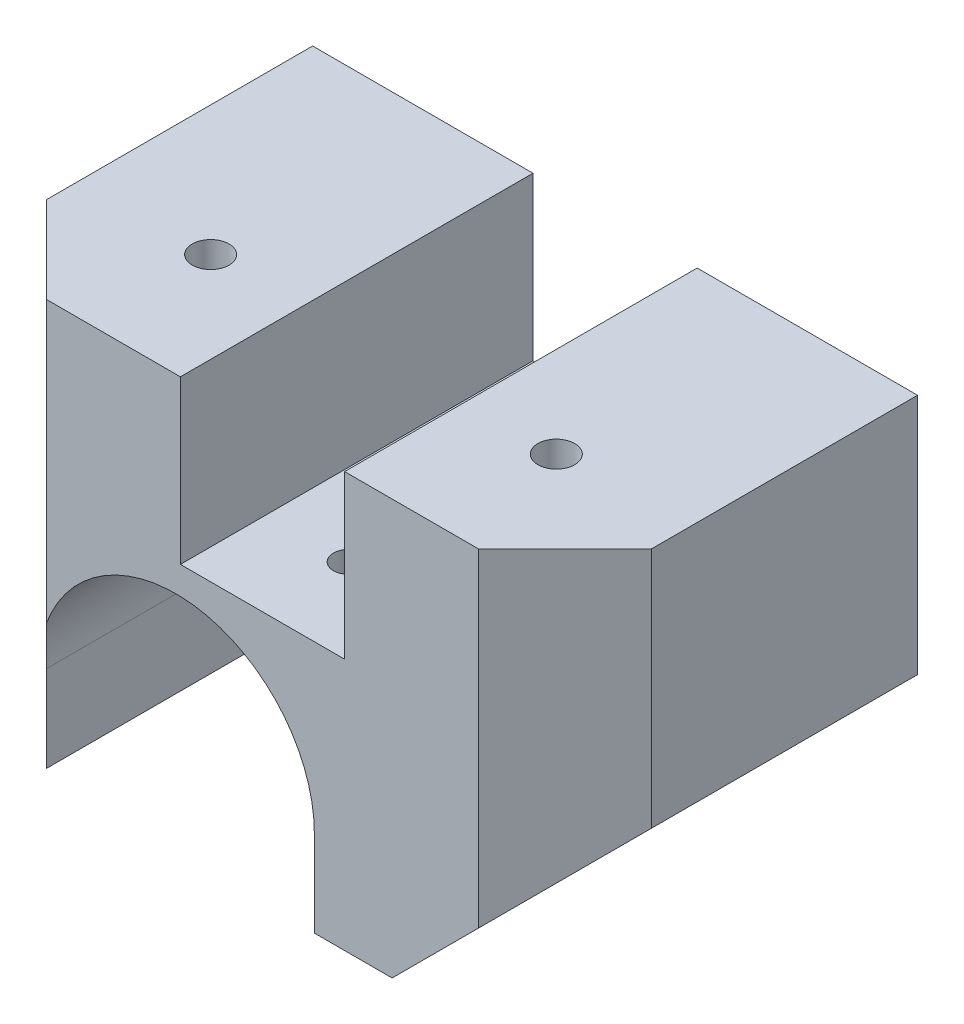
SolidWorks part; units mm, degrees
material "Nylon 6/10"
ref_plane "Front Plane" through (0, 0, 0) normal (0, 0, 1) x (1, 0, 0)
ref_plane "Top Plane" through (0, 0, 0) normal (0, 1, 0) x (1, 0, 0)
ref_plane "Right Plane" through (0, 0, 0) normal (1, 0, 0) x (0, 0, -1)
sketch "Sketch1" plane through (0, 0, 0) normal (0, 1, 0) x (1, 0, 0)
  line L1 (-22.225, -12.954) -> (22.225, -12.954)
  line L2 (-22.225, -12.954) -> (-22.225, 12.954)
  line L3 (-22.225, 12.954) -> (22.225, 12.954)
  line L4 (22.225, -12.954) -> (22.225, 12.954)
  line L5 (-22.225, -12.954) -> (22.225, 12.954) construction
  line L6 (-22.225, 12.954) -> (22.225, -12.954) construction
  point P0 (0, 0)
  dimension "D1" = 25.908
  dimension "D2" = 44.45
extrude "Boss-Extrude1" add sketch "Sketch1" along normal blind 30.48
chamfer "SideChamfer" distance 12.7 angle 45 1 edges at (22.225, 0, 0)
chamfer "BackChamfers" distance 6.35 angle 45 2 edges at (-22.225, 15.24, 12.954) (22.225, 21.59, 12.954)
sketch "Sketch2" plane through (0, 0, 12.954) normal (0, 0, 1) x (1, 0, 0)
  line L1 (-6.0325, 30.48) -> (6.0325, 30.48)
  line L2 (-6.0325, 30.48) -> (-6.0325, 18.542)
  line L3 (-6.0325, 18.542) -> (6.0325, 18.542)
  line L4 (6.0325, 30.48) -> (6.0325, 18.542)
  line L5 (-6.0325, 30.48) -> (6.0325, 18.542) construction
  line L6 (-6.0325, 18.542) -> (6.0325, 30.48) construction
  line L7 (0, 18.542) -> (0, 30.48) construction
  line L8 (-15.875, 30.48) -> (15.875, 30.48) construction
  point P0 (0, 24.511)
  dimension "D1" = 11.938
  dimension "D2" = 12.065
extrude "LinActSlot" cut sketch "Sketch2" against normal through all
hole_wizard "MoutingHoles" positions "Sketch4" profile "Sketch3" tap size "#6-32" standard "ANSI Inch"
sketch "Sketch4" plane through (14.1604, 30.48, 8.3734) normal (0, -1, 0) x (-1, 0, 0)
  line L0 (14.1604, 8.3734) -> (14.1604, 11.4563) construction
  line L3 (30.0354, -4.5806) -> (20.1929, -4.5806) construction
  point P0 (1.4604, 4.3094)
  point P2 (26.8604, 4.3094)
  dimension "D1" = 25.4
  dimension "D2" = 8.89
sketch "Sketch3" plane through (12.7, 30.48, 4.064) normal (1, 0, 0) x (0, 0, 1)
  line L0 (0, 0) -> (0, 15.2907)
  line L1 (0, 15.2907) -> (1.3525, 14.478)
  line L2 (1.3525, 14.478) -> (1.3525, 0)
  line L5 (1.3525, 0) -> (0, 0)
  line L10 (0, 15.2907) -> (-1.3526, 14.478) construction
  line L11 (0, -6.35) -> (0, 107.95) construction
  dimension "Tap Drill Dia." = 2.7051
  dimension "Tap Drill Depth" = 14.478
  dimension "Drill Angle" = 118
sketch "Sketch5" plane through (0, 0, -12.954) normal (0, 0, -1) x (-1, 0, 0)
  line L0 (-9.525, 0) -> (22.225, 0) construction
  line L2 (16.51, 0) -> (-3.81, 0)
  line L3 (16.51, 0) -> (16.51, 7.747)
  line L4 (7.62, 16.637) -> (5.08, 16.637)
  line L6 (-3.81, 0) -> (-3.81, 7.747)
  line L8 (22.225, 30.48) -> (22.225, 0) construction
  arc A0 (-3.81, 7.747) -> (5.08, 16.637) centre (5.08, 7.747) cw
  arc A1 (16.51, 7.747) -> (7.62, 16.637) centre (7.62, 7.747) ccw
  point P8 (6.35, 0)
  dimension "D2" = 16.637
  dimension "D4" = 8.89
  dimension "D1" = 20.32
  dimension "D3" = 15.875
extrude "MotorSlot" [suppressed] cut sketch "Sketch5" against normal through all
hole_wizard "MotorMountingHoles" [suppressed] positions "Sketch7" profile "Sketch6" tap size "#4-40" standard "ANSI Inch"
sketch "Sketch7" [suppressed] plane through (0, 0, -12.954) normal (0, 0, -1) x (-1, 0, 0)
  line L2 (7.62, 16.637) -> (5.08, 16.637) construction
  line L3 (7.62, 16.637) -> (5.08, 16.637) construction
  line L4 (6.35, 16.637) -> (6.35, -5.5191) construction
  line L6 (6.0325, 30.48) -> (22.225, 30.48) construction
  point P0 (18.8468, 6.35)
  point P8 (-6.1468, 6.35)
  dimension "D1" = 24.13
  dimension "D3" = 24.9936
sketch "Sketch6" plane through (-18.8468, 6.35, -12.954) normal (1, 0, 0) x (0, 1, 0)
  line L0 (0, 0) -> (0, 9.5692)
  line L1 (0, 9.5692) -> (1.1303, 8.89)
  line L2 (1.1303, 8.89) -> (1.1303, 0)
  line L5 (1.1303, 0) -> (0, 0)
  line L10 (0, 9.5692) -> (-1.1303, 8.89) construction
  line L11 (0, -6.35) -> (0, 107.95) construction
  dimension "Tap Drill Dia." = 2.2606
  dimension "Tap Drill Depth" = 8.89
  dimension "Drill Angle" = 118
cosmetic thread "Hole Thread1" parameters "D1"=6.858, "D2"=2.8448
cosmetic thread "Hole Thread2" parameters "D1"=6.858, "D2"=2.8448
sketch "Sketch11" plane through (0, 0, -12.954) normal (0, 0, -1) x (-1, 0, 0)
  line L0 (-9.525, 0) -> (22.225, 0) construction
  line L3 (22.225, 30.48) -> (22.225, 0) construction
  line L4 (16.51, 6.35) -> (16.51, 0)
  line L5 (-9.525, 0) -> (22.225, 0) construction
  line L6 (16.51, 0) -> (-3.81, 0)
  line L7 (-3.81, 0) -> (-3.81, 6.35)
  arc A0 (16.51, 6.35) -> (-3.81, 6.35) centre (6.35, 6.35) ccw
  dimension "D1" = 20.32
  dimension "D2" = 6.35
  dimension "D3" = 15.875
extrude "Cut-Extrude1" cut sketch "Sketch11" against normal through all
hole_wizard "MotorMountingHoles2" positions "Sketch13" profile "Sketch12" tap size "#4-40" standard "ANSI Inch"
sketch "Sketch13" plane through (0, 0, -12.954) normal (0, 0, -1) x (-1, 0, 0)
  line L0 (6.35, 6.35) -> (6.35, -5.2471) construction
  arc A0 (16.51, 6.35) -> (-3.81, 6.35) centre (6.35, 6.35) ccw construction
  arc A1 (16.51, 6.35) -> (-3.81, 6.35) centre (6.35, 6.35) ccw construction
  point P0 (18.8468, 6.35)
  point P2 (-6.1468, 6.35)
  dimension "D1" = 24.9936
sketch "Sketch12" plane through (-18.8468, 6.35, -12.954) normal (1, 0, 0) x (0, 1, 0)
  line L0 (0, 0) -> (0, 12.1092)
  line L1 (0, 12.1092) -> (1.1303, 11.43)
  line L2 (1.1303, 11.43) -> (1.1303, 0)
  line L5 (1.1303, 0) -> (0, 0)
  line L10 (0, 12.1092) -> (-1.1303, 11.43) construction
  line L11 (0, -6.35) -> (0, 107.95) construction
  dimension "Tap Drill Dia." = 2.2606
  dimension "Tap Drill Depth" = 11.43
  dimension "Drill Angle" = 118
cosmetic thread "Hole Thread4" parameters "D1"=9.398, "D2"=2.8448
cosmetic thread "Hole Thread5" parameters "D1"=9.398, "D2"=2.8448
hole_wizard "GripperSetScrew" positions "Sketch15" profile "Sketch14" tap size "#4-40" standard "ANSI Inch" end condition through all
sketch "Sketch15" plane through (0, 18.542, 0) normal (0, 1, 0) x (1, 0, 0)
  line L0 (0, 0) -> (0, -12.954) construction
  line L1 (-6.0325, -12.954) -> (6.0325, -12.954) construction
  point P0 (0, -6.604)
  dimension "D1" = 6.35
sketch "Sketch14" plane through (0, 18.542, 6.604) normal (1, 0, 0) x (0, 0, 1)
  line L0 (0, 0) -> (0, 18.542)
  line L1 (0, 18.542) -> (1.1303, 18.542)
  line L2 (1.1303, 18.542) -> (1.1303, 0)
  line L5 (1.1303, 0) -> (0, 0)
  line L11 (0, -6.35) -> (0, 107.95) construction
  dimension "Thru Tap Drill Dia." = 2.2606
  dimension "Thru Tap Drill Depth" = 18.542
cosmetic thread "Hole Thread6" parameters "D2"=2.8448
